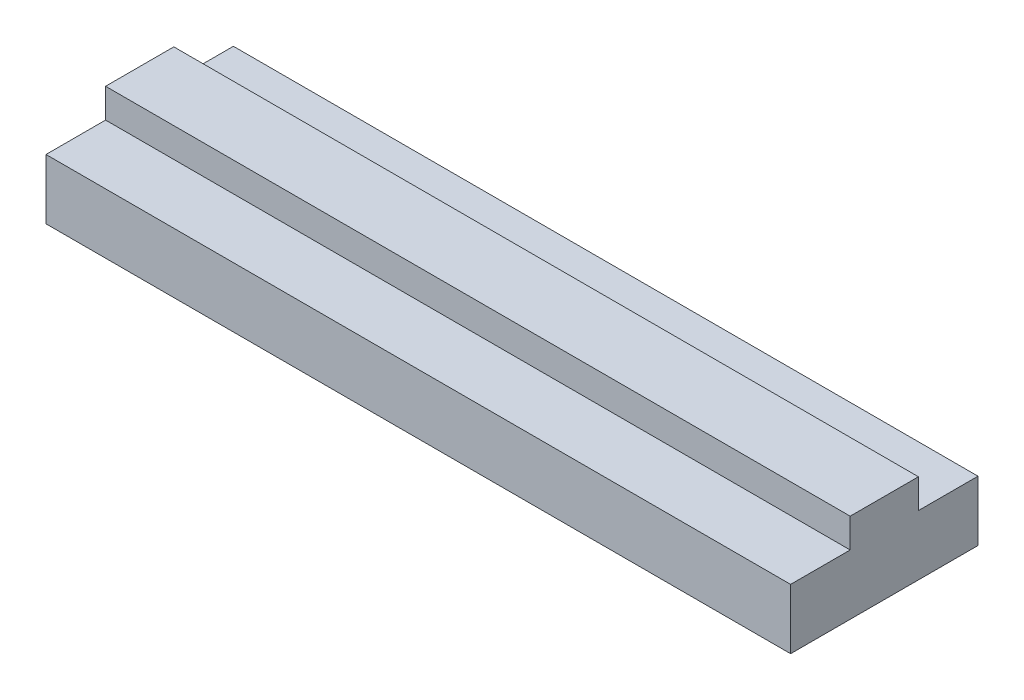
SolidWorks part; units mm, degrees
ref_plane "Front Plane" through (0, 0, 0) normal (0, 0, 1) x (1, 0, 0)
ref_plane "Top Plane" through (0, 0, 0) normal (0, 1, 0) x (1, 0, 0)
ref_plane "Right Plane" through (0, 0, 0) normal (1, 0, 0) x (0, 0, -1)
sketch "Sketch1" plane through (0, 0, 0) normal (0, 1, 0) x (1, 0, 0)
  line L1 (75, -18.875) -> (-75, -18.875)
  line L2 (75, -18.875) -> (75, 18.875)
  line L3 (75, 18.875) -> (-75, 18.875)
  line L4 (-75, -18.875) -> (-75, 18.875)
  line L5 (75, -18.875) -> (-75, 18.875) construction
  line L6 (75, 18.875) -> (-75, -18.875) construction
  point P0 (0, 0)
  dimension "D1" = 150
  dimension "D2" = 37.75
extrude "Boss-Extrude1" add sketch "Sketch1" along normal blind 18
sketch "Sketch2" plane through (75, 0, 0) normal (1, 0, 0) x (0, 0, -1)
  line L1 (-6.875, 12.1) -> (-18.875, 12.1)
  line L2 (-6.875, 12.1) -> (-6.875, 18)
  line L3 (-6.875, 18) -> (-18.875, 18)
  line L4 (-18.875, 12.1) -> (-18.875, 18)
  line L5 (-6.875, 12.1) -> (-18.875, 18) construction
  line L6 (-6.875, 18) -> (-18.875, 12.1) construction
  point P0 (-12.875, 15.05)
  dimension "D1" = 12
  dimension "D2" = 5.9
extrude "Cut-Extrude1" cut sketch "Sketch2" against normal up to surface (150 mm away) up to face at (-75, 9, 0)
sketch "Sketch3" plane through (75, 0, 0) normal (1, 0, 0) x (0, 0, -1)
  line L0 (-6.875, 18) -> (18.875, 18) construction
  line L1 (6.875, 12.1) -> (18.875, 12.1)
  line L2 (6.875, 12.1) -> (6.875, 18)
  line L3 (6.875, 18) -> (18.875, 18)
  line L4 (18.875, 12.1) -> (18.875, 18)
  line L5 (6.875, 12.1) -> (18.875, 18) construction
  line L6 (6.875, 18) -> (18.875, 12.1) construction
  line L7 (18.875, 18) -> (18.875, 0) construction
  point P0 (12.875, 15.05)
  dimension "D1" = 12
  dimension "D2" = 5.9
extrude "Cut-Extrude2" cut sketch "Sketch3" against normal up to surface (150 mm away) up to face at (-75, 10.0333, 2.2917)
sketch "Sketch4" plane through (0, 0, 0) normal (0, -1, 0) x (1, 0, 0)
  line L1 (70.1, -5.1) -> (-70.1, -5.1)
  line L2 (70.1, -5.1) -> (70.1, 5.1)
  line L3 (70.1, 5.1) -> (-70.1, 5.1)
  line L4 (-70.1, -5.1) -> (-70.1, 5.1)
  line L5 (70.1, -5.1) -> (-70.1, 5.1) construction
  line L6 (70.1, 5.1) -> (-70.1, -5.1) construction
  point P0 (0, 0)
  dimension "D1" = 140.2
  dimension "D2" = 10.2
extrude "Cut-Extrude3" cut sketch "Sketch4" against normal blind 7.5
